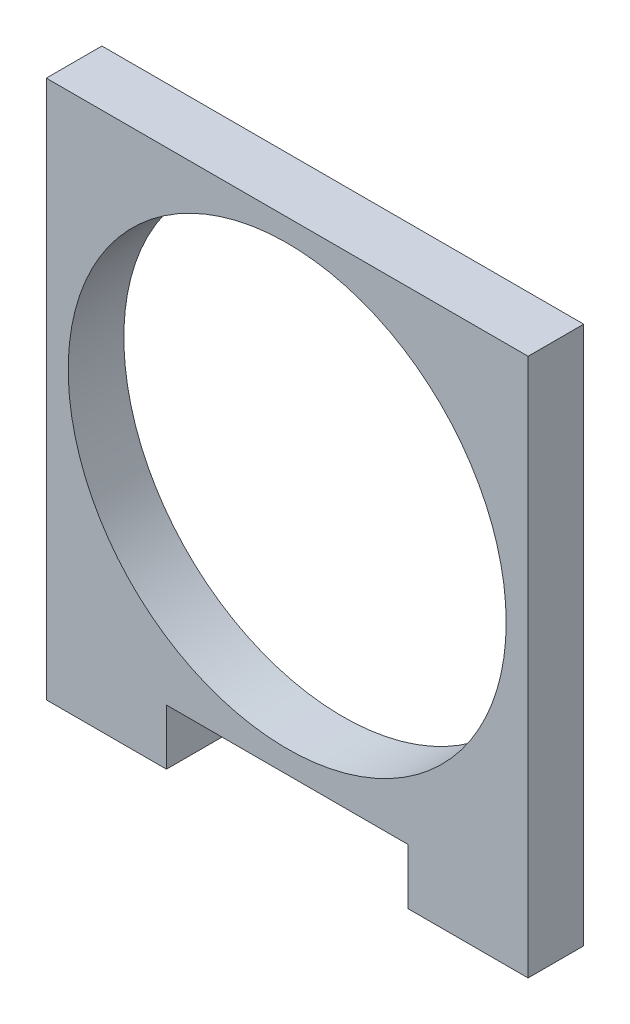
SolidWorks part; units mm, degrees
ref_plane "Front Plane" through (0, 0, 0) normal (0, 0, 1) x (1, 0, 0)
ref_plane "Top Plane" through (0, 0, 0) normal (0, 1, 0) x (1, 0, 0)
ref_plane "Right Plane" through (0, 0, 0) normal (1, 0, 0) x (0, 0, -1)
sketch "Sketch2" plane through (0, 0, 0) normal (0, 0, 1) x (1, 0, 0)
  line L0 (27.5, 55.118) -> (27.5, 0) construction
  line L1 (13.716, 0) -> (41.284, 0)
  line L2 (0, 0) -> (0, 55.118)
  line L3 (0, 55.118) -> (55, 55.118)
  line L4 (55, 0) -> (55, 55.118)
  line L6 (0, 0) -> (0, -6.35)
  line L7 (0, -6.35) -> (13.716, -6.35)
  line L8 (13.716, 0) -> (13.716, -6.35)
  line L9 (41.284, 0) -> (41.284, -6.35)
  line L10 (55, -6.35) -> (41.284, -6.35)
  line L11 (55, 0) -> (55, -6.35)
  dimension "D1" = 6.35
  dimension "D2" = 55
  dimension "D3" = 55.118
  dimension "D4" = 13.716
extrude "Boss-Extrude1" add sketch "Sketch2" along normal blind 6.35
sketch "Sketch3" plane through (0, 0, 6.35) normal (0, 0, 1) x (1, 0, 0)
  line L0 (27.5, 55.118) -> (27.5, 0) construction
  line L1 (55, 55.118) -> (0, 55.118) construction
  line L2 (13.716, 0) -> (41.284, 0) construction
  line L3 (0, 27.559) -> (55, 27.559) construction
  line L4 (0, 55.118) -> (0, -6.35) construction
  line L5 (55, -6.35) -> (55, 55.118) construction
  circle A0 centre (27.5, 27.559) radius 25
  dimension "D1" = 50
extrude "Cut-Extrude1" cut sketch "Sketch3" against normal through all both and the other way through all
equation "\"Wheel Thickness\"= 1in"
equation "\"Wheel Diameter\"= 3in"
equation "\"Motor Rear Diameter\" = 36.2mm"
equation "\"Motor Front Diameter\" = 12mm"
equation "\"Material Thickness\" = .25in"
equation "\"Wheel Cutout Diameter\"= 2cm"
equation "\"Motor Mount Tab Thickness\" = 100mm"
equation "\"Motor Mount Tab Height\" = 40mm"
equation "\"Motor Shaft Diameter\" = 3mm"
equation "\"Wheel Radius Clearance\" = 5mm"
equation "\"Wheel Cutout Width\" = 1.5in"
equation "\"Base Diameter\" = 10in"
equation "\"Wheel Mount Distance\" = 5mm"
equation "\"Motor Mount Distance\" = 50mm"
equation "\"Motor Cutout Length\" = 6in"
equation "\"Motor Cutout Height\" = 2in "
equation "\"Rod Diameter\" = 3/8in"
equation "\"Rod Length\" = 1.5in"
equation "\"Barrel Front Length\" = 1.8in"
equation "\"Barrerl Rear Length\" = 5in "
equation "\"Barrel Fillet Radius\" = 1in "
equation "\"Barrel Angle\" = 20deg"
equation "\"Barrel Diameter\" = 50mm"
equation "\"Barrel Shell Width\" = 2mm"
equation "\"Second Level Diameter\" = 10in"
equation "\"Ball Diameter\" = 40mm"
equation "\"Third Level Length\" = 9in"
equation "\"Third Level Height\" = 9in"
equation "\"Barrel Tab Clearance\" = 5mm"
equation "\"Barrel Tab Distance Away\" = 2mm"
equation "\"Hole Distance Apart\" = 2.8in"
equation "\"Barrel Tab Distance\"= 1.5in "
equation "\"D1@Sketch2\"=\"Material Thickness\""
equation "\"D2@Sketch2\"=\"Barrel Diameter\"+\"Barrel Tab Clearance\""
equation "\"D1@Boss-Extrude1\"=\"Material Thickness\""
equation "\"D1@Sketch3\"=\"Barrel Diameter\""
